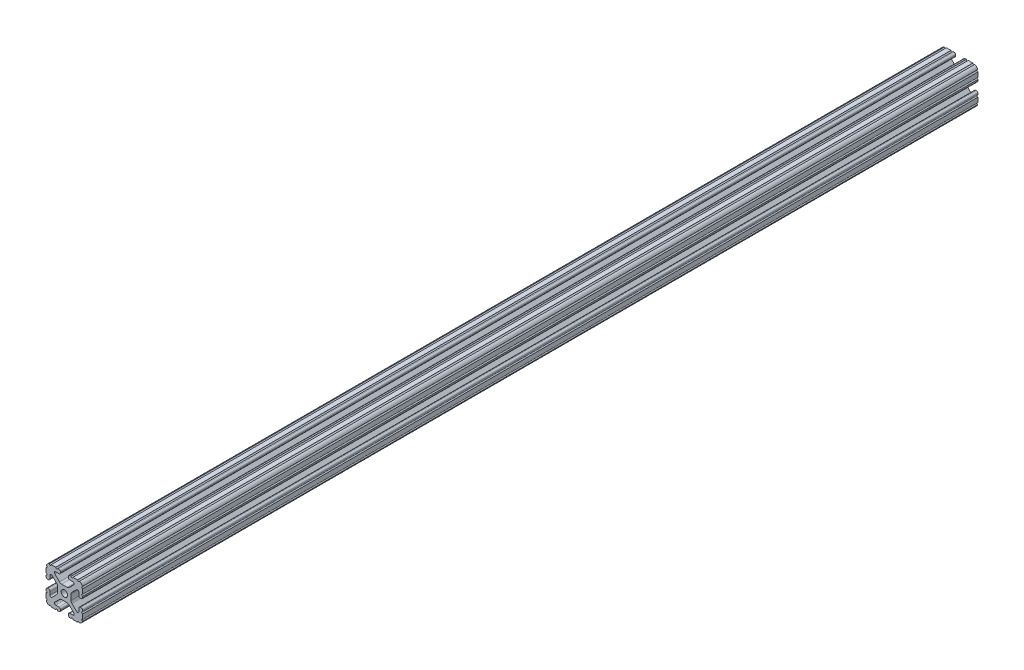
SolidWorks part; units mm, degrees
ref_plane "Front Plane" through (0, 0, 0) normal (0, 0, 1) x (1, 0, 0)
ref_plane "Top Plane" through (0, 0, 0) normal (0, 1, 0) x (1, 0, 0)
ref_plane "Right Plane" through (0, 0, 0) normal (1, 0, 0) x (0, 0, -1)
sketch "Sketch2" plane through (0, 0, 0) normal (0, 0, 1) x (1, 0, 0)
  line L0 (0, 19.05) -> (0, -19.05) construction
  line L1 (-19.05, 0) -> (19.05, 0) construction
  line L2 (4.064, -19.05) -> (19.05, -19.05)
  line L3 (19.05, -19.05) -> (19.05, -4.064)
  line L4 (4.064, -19.05) -> (4.064, -14.986)
  line L5 (4.064, -14.986) -> (12.1123, -14.986)
  line L6 (12.1123, -14.986) -> (4.1113, -6.985)
  line L7 (0, 0) -> (19.05, -19.05) construction
  line L8 (19.05, -4.064) -> (14.986, -4.064)
  line L9 (14.986, -4.064) -> (14.986, -12.1123)
  line L10 (14.986, -12.1123) -> (6.985, -4.1113)
  circle A0 centre (0, 0) radius 3.3274
  arc A1 (8.9963, -14.986) -> (9.909, -12.7826) centre (8.9963, -13.6953) ccw construction
  point P8 (0, -6.985)
  dimension "Center Hole Diameter" = 6.6548
  dimension "Rail Height" = 38.1
  dimension "Rail Width" = 38.1
  dimension "T-Slot Width" = 8.128
  dimension "Slot Inner Width" = 20.574
  dimension "Thickness" = 4.064
  dimension "Slot Depth" = 8.001
  dimension "D1" = 4.064
sketch "Sketch3" plane through (0, 0, 0) normal (1, 0, 0) x (0, 0, -1)
  line L0 (-465, -19.05) -> (465, -19.05) construction
  line L1 (-439.6, 0) -> (439.6, 0) construction
  dimension "Length" = 930
  dimension "D1" = 25.4
sketch "Sketch4" plane through (0, 0, 0) normal (0, 0, 1) x (1, 0, 0)
  line L0 (5.7912, -19.05) -> (14.3002, -19.05)
  line L1 (4.064, -19.05) -> (19.05, -19.05) construction
  line L2 (4.064, -19.05) -> (4.064, -14.986) construction
  line L3 (4.064, -14.986) -> (12.1123, -14.986) construction
  line L4 (4.064, -16.7132) -> (4.064, -17.3228)
  line L5 (5.7912, -14.986) -> (8.9963, -14.986)
  line L6 (0, -6.985) -> (2.833, -6.985)
  line L7 (12.1123, -14.986) -> (4.1113, -6.985) construction
  line L8 (5.0152, -7.8889) -> (9.909, -12.7826)
  line L9 (19.05, -19.05) -> (19.05, -4.064) construction
  line L10 (14.986, -12.1123) -> (6.985, -4.1113) construction
  line L11 (14.986, -4.064) -> (14.986, -12.1123) construction
  line L12 (14.986, -8.9963) -> (14.986, -5.7912)
  line L13 (19.05, -4.064) -> (14.986, -4.064) construction
  line L14 (16.7132, -4.064) -> (17.3228, -4.064)
  line L15 (19.05, -5.7912) -> (19.05, -14.3002)
  line L16 (12.7826, -9.909) -> (7.8889, -5.0152)
  line L17 (6.985, 0) -> (6.985, -2.833)
  line L18 (-19.05, 0) -> (19.05, 0) construction
  line L19 (0, -6.985) -> (0, -3.3274)
  line L20 (0, 19.05) -> (0, -19.05) construction
  line L21 (6.985, 0) -> (3.3274, 0)
  arc A0 (4.064, -17.3228) -> (5.7912, -19.05) centre (5.7912, -17.3228) ccw
  arc A2 (4.064, -16.7132) -> (5.7912, -14.986) centre (5.7912, -16.7132) cw
  arc A3 (8.9963, -14.986) -> (9.909, -12.7826) centre (8.9963, -13.6953) ccw
  arc A4 (2.833, -6.985) -> (5.0152, -7.8889) centre (2.833, -10.0711) cw
  arc A5 (14.3002, -19.05) -> (19.05, -14.3002) centre (14.3002, -14.3002) ccw
  arc A6 (12.7826, -9.909) -> (14.986, -8.9963) centre (13.6953, -8.9963) ccw
  arc A7 (14.986, -5.7912) -> (16.7132, -4.064) centre (16.7132, -5.7912) cw
  arc A8 (17.3228, -4.064) -> (19.05, -5.7912) centre (17.3228, -5.7912) cw
  arc A9 (7.8889, -5.0152) -> (6.985, -2.833) centre (10.0711, -2.833) cw
  circle A10 centre (0, 0) radius 3.3274 construction
  arc A11 (0, -3.3274) -> (3.3274, 0) centre (0, 0) ccw
  dimension "D1" = 4.7498
  dimension "D2" = 3.0861
  dimension "D3" = 1.7272
extrude "Boss-Extrude1" add sketch "Sketch4" along normal mid plane 930
sketch "Sketch5" plane through (0, 0, 0) normal (0, 0, 1) x (1, 0, 0)
  line L0 (4.064, -19.05) -> (19.05, -19.05) construction
  line L1 (5.7912, -14.986) -> (8.9963, -14.986) construction
  line L3 (0, 0) -> (19.05, -19.05) construction
  line L4 (8.9963, -14.986) -> (8.9963, -19.05) construction
  line L5 (12.1123, -14.986) -> (4.1113, -6.985) construction
  circle A0 centre (14.7395, -19.05) radius 1.016
  circle A1 centre (7.9803, -19.05) radius 1.016
  circle A2 centre (19.05, -14.7395) radius 1.016
  circle A3 centre (19.05, -7.9803) radius 1.016
  point P10 (7.3938, -14.986)
  point P12 (13.6953, -8.9963)
  dimension "D1" = 2.032
extrude "Cut-Extrude1" cut sketch "Sketch5" against normal through all both and the other way through all
mirror "Mirror1" about plane through (0, 0, 0) normal (1, 0, 0) of bodies 137 134
mirror "Mirror2" about plane through (0, 0, 0) normal (0, 1, 0) of bodies 135
equation "\"D1@Boss-Extrude1\"=\"Length@Sketch3\""
equation "\"D1@Sketch2\"=\"Thickness@Sketch2\""
equation "\"D2@Sketch4\"=\"Slot Inner Width@Sketch2\"*0.15"
equation "\"D1@Sketch4\"=\"D3@Sketch4\"*2.75"
equation "\"D3@Sketch4\"=\"Thickness@Sketch2\"*0.425"
equation "\"D1@Sketch5\"=\"Thickness@Sketch2\"*0.5"
